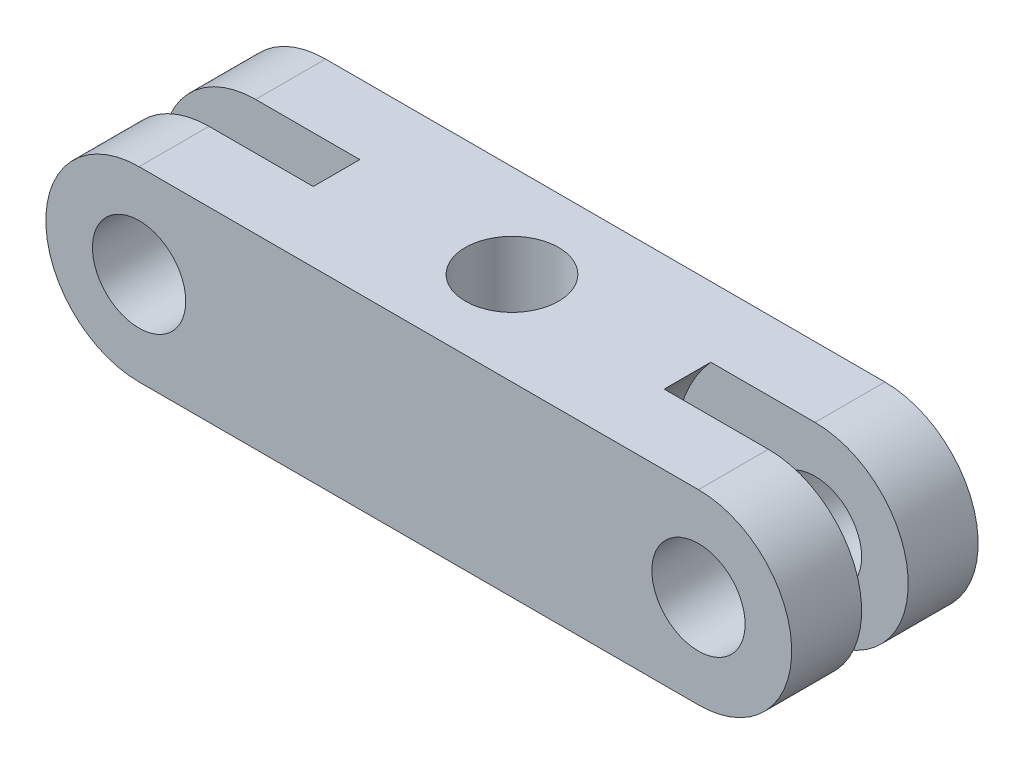
SolidWorks part; units mm, degrees
ref_plane "Front Plane" through (0, 0, 0) normal (0, 0, 1) x (1, 0, 0)
ref_plane "Top Plane" through (0, 0, 0) normal (0, 1, 0) x (1, 0, 0)
ref_plane "Right Plane" through (0, 0, 0) normal (1, 0, 0) x (0, 0, -1)
sketch "Sketch1" plane through (0, 0, 0) normal (0, 0, 1) x (1, 0, 0)
  line L0 (0, 0) -> (60, 0) construction
  line L1 (0, 10) -> (60, 10)
  line L2 (0, -10) -> (60, -10)
  arc A0 (0, 10) -> (0, -10) centre (0, 0) ccw
  arc A1 (60, -10) -> (60, 10) centre (60, 0) ccw
  circle A2 centre (0, 0) radius 5
  circle A3 centre (60, 0) radius 5
  point P3 (30, 0)
  dimension "D2" = 10
  dimension "D3" = 10
  dimension "D1" = 60
  dimension "D4" = 20
extrude "Boss-Extrude1" add sketch "Sketch1" along normal mid plane 20
sketch "Sketch3" plane through (0, 0, 0) normal (0, 0, 1) x (1, 0, 0)
  circle A0 centre (0, 0) radius 15
  circle A1 centre (60, 0) radius 15
  dimension "D1" = 30
  dimension "D2" = 30
extrude "Cut-Extrude2" cut sketch "Sketch3" against normal mid plane 5
sketch "Sketch4" plane through (0, 10, 0) normal (0, 1, 0) x (1, 0, 0)
  line L0 (11.1803, 0) -> (48.8197, 0) construction
  line L1 (11.1803, 2.5) -> (11.1803, -2.5) construction
  line L2 (48.8197, -2.5) -> (48.8197, 2.5) construction
  circle A0 centre (30, 0) radius 5
  dimension "D1" = 10
extrude "Cut-Extrude3" cut sketch "Sketch4" against normal through all
